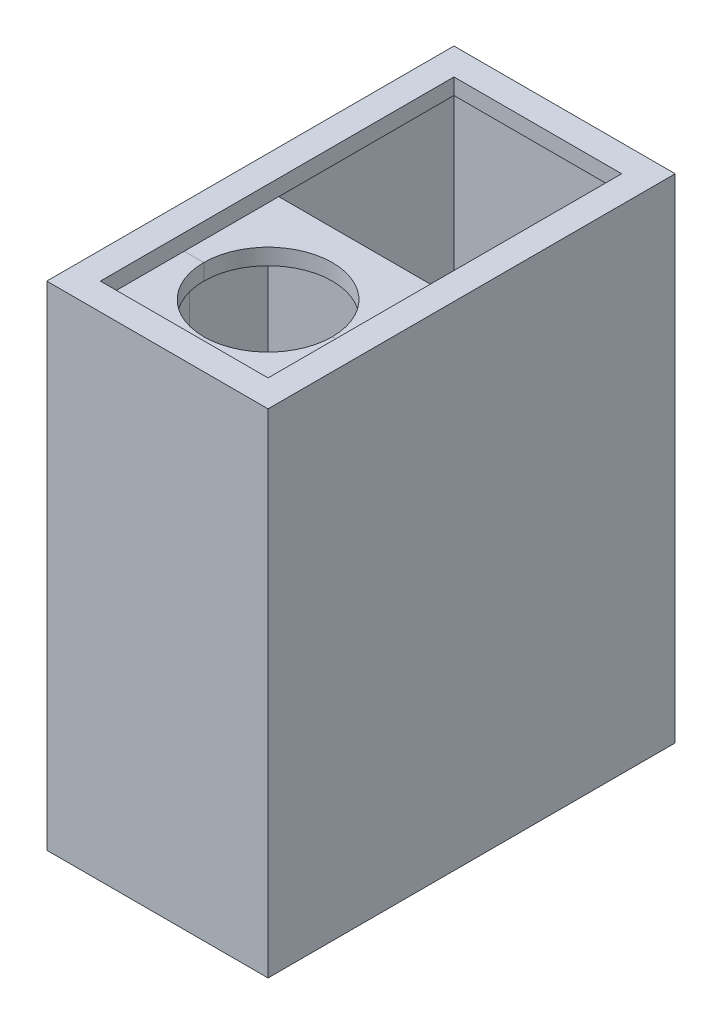
SolidWorks part; units mm, degrees
ref_plane "Front Plane" through (0, 0, 0) normal (0, 0, 1) x (1, 0, 0)
ref_plane "Top Plane" through (0, 0, 0) normal (0, 1, 0) x (1, 0, 0)
ref_plane "Right Plane" through (0, 0, 0) normal (1, 0, 0) x (0, 0, -1)
sketch "Sketch1" plane through (0, 0, 0) normal (0, 1, 0) x (1, 0, 0)
  line L1 (14.65, -14.65) -> (-14.65, -14.65)
  line L2 (14.65, -14.65) -> (14.65, 14.65)
  line L3 (14.65, 14.65) -> (-14.65, 14.65)
  line L4 (-14.65, -14.65) -> (-14.65, 14.65)
  line L5 (14.65, -14.65) -> (-14.65, 14.65) construction
  line L6 (14.65, 14.65) -> (-14.65, -14.65) construction
  point P0 (0, 0)
  dimension "D1" = 29.3
  dimension "D2" = 29.3
extrude "Extrude-Thin1" add sketch "Sketch1" along normal blind 20 thin thin type one direction wall 3
sketch "Sketch2" plane through (0, 0, 0) normal (0, -1, 0) x (1, 0, 0)
  line L1 (-17.65, 17.65) -> (17.65, 17.65)
  line L2 (-17.65, 17.65) -> (-17.65, -17.65)
  line L3 (-17.65, -17.65) -> (17.65, -17.65)
  line L4 (17.65, 17.65) -> (17.65, -17.65)
  line L5 (-17.65, 17.65) -> (17.65, -17.65) construction
  line L6 (-17.65, -17.65) -> (17.65, 17.65) construction
  point P0 (0, 0)
extrude "Boss-Extrude3" add sketch "Sketch2" along normal blind 3 separate body
sketch "Sketch3" plane through (17.65, 0, 0) normal (1, 0, 0) x (0, 0, -1)
  line L5 (-17.65, 0) -> (17.65, 0) construction
  line L6 (-17.65, 20) -> (17.65, 20) construction
  line L7 (-5, 6) -> (5, 6)
  line L8 (-5, 6) -> (-5, 3)
  line L9 (-5, 3) -> (5, 3)
  line L10 (5, 6) -> (5, 3)
  line L11 (-5, 6) -> (5, 3) construction
  line L12 (-5, 3) -> (5, 6) construction
  point P0 (0, 4.5)
  point P8 (0, 0)
  dimension "D1" = 10
  dimension "D2" = 14
  dimension "D3" = 3
  dimension "D4" = 0
extrude "Cut-Extrude1" cut sketch "Sketch3" against normal up to next (3 mm away)
sketch "Sketch5" plane through (0, 20, 0) normal (0, 1, 0) x (1, 0, 0)
  line L1 (14.65, -14.65) -> (-14.65, -14.65)
  line L2 (14.65, -14.65) -> (14.65, 14.65)
  line L3 (14.65, 14.65) -> (-14.65, 14.65)
  line L4 (-14.65, -14.65) -> (-14.65, 14.65)
  line L5 (14.65, -14.65) -> (-14.65, 14.65) construction
  line L6 (14.65, 14.65) -> (-14.65, -14.65) construction
  point P0 (0, 0)
extrude "Extrude-Thin2" add sketch "Sketch5" along normal blind 60 separate body thin thin type one direction wall 3
sketch "Sketch6" plane through (0, 80, 0) normal (0, 1, 0) x (1, 0, 0)
  line L1 (17.65, -17.65) -> (-17.65, -17.65)
  line L2 (17.65, -17.65) -> (17.65, 17.65)
  line L3 (17.65, 17.65) -> (-17.65, 17.65)
  line L4 (-17.65, -17.65) -> (-17.65, 17.65)
  line L5 (17.65, -17.65) -> (-17.65, 17.65) construction
  line L6 (17.65, 17.65) -> (-17.65, -17.65) construction
  point P0 (0, 0)
extrude "Boss-Extrude4" add sketch "Sketch6" along normal blind 3
sketch "Sketch7" plane through (0, 83, 0) normal (0, 1, 0) x (1, 0, 0)
  circle A0 centre (0, 0) radius 12
extrude "Cut-Extrude2" cut sketch "Sketch7" against normal up to next (3 mm away)
sketch "Sketch9" plane through (-17.65, 0, 0) normal (-1, 0, 0) x (0, 0, 1)
  line L0 (0, 83) -> (0, 20)
  line L1 (-17.65, 83) -> (17.65, 83) construction
  line L2 (-17.65, 20) -> (17.65, 20) construction
split "Split1" trim tools "Sketch9" bodies to split 108 resulting bodies 109 110
sketch "Sketch10" plane through (0, 0, 17.65) normal (0, 0, 1) x (1, 0, 0)
  line L1 (17.65, -3) -> (-17.65, -3)
  line L2 (17.65, -3) -> (17.65, 83)
  line L3 (17.65, 83) -> (-17.65, 83)
  line L4 (-17.65, -3) -> (-17.65, 83)
extrude "Extrude-Thin4" add sketch "Sketch10" against normal blind 70 separate body thin thin type one direction wall 3
sketch "Sketch15" plane through (0, 0, 17.65) normal (0, 0, 1) x (1, 0, 0)
  line L1 (20.65, 86) -> (-20.65, 86)
  line L2 (20.65, 86) -> (20.65, -6)
  line L3 (20.65, -6) -> (-20.65, -6)
  line L4 (-20.65, 86) -> (-20.65, -6)
extrude "Boss-Extrude7" add sketch "Sketch15" along normal blind 3
sketch "Sketch16" plane through (0, 0, -52.35) normal (0, 0, -1) x (-1, 0, 0)
  line L1 (-20.65, 86) -> (20.65, 86)
  line L2 (-20.65, 86) -> (-20.65, -6)
  line L3 (-20.65, -6) -> (20.65, -6)
  line L4 (20.65, 86) -> (20.65, -6)
extrude "Boss-Extrude8" add sketch "Sketch16" along normal blind 3
sketch "Sketch17" plane through (0, 86, 0) normal (0, 1, 0) x (1, 0, 0)
  line L0 (-15.65, 50.35) -> (-15.65, -15.65)
  line L1 (-20.65, 55.35) -> (20.65, 55.35)
  line L2 (-20.65, 55.35) -> (-20.65, -20.65)
  line L3 (-20.65, -20.65) -> (20.65, -20.65)
  line L4 (20.65, 55.35) -> (20.65, -20.65)
  line L5 (-15.65, -15.65) -> (15.65, -15.65)
  line L6 (15.65, 50.35) -> (15.65, -15.65)
  line L7 (-15.65, 50.35) -> (15.65, 50.35)
  dimension "D1" = 5
extrude "Cut-Extrude6" cut sketch "Sketch17" against normal up to next (3 mm away) contours L0 L5 L6 L7
other "Save Bodies1"
other "Save Bodies2"
